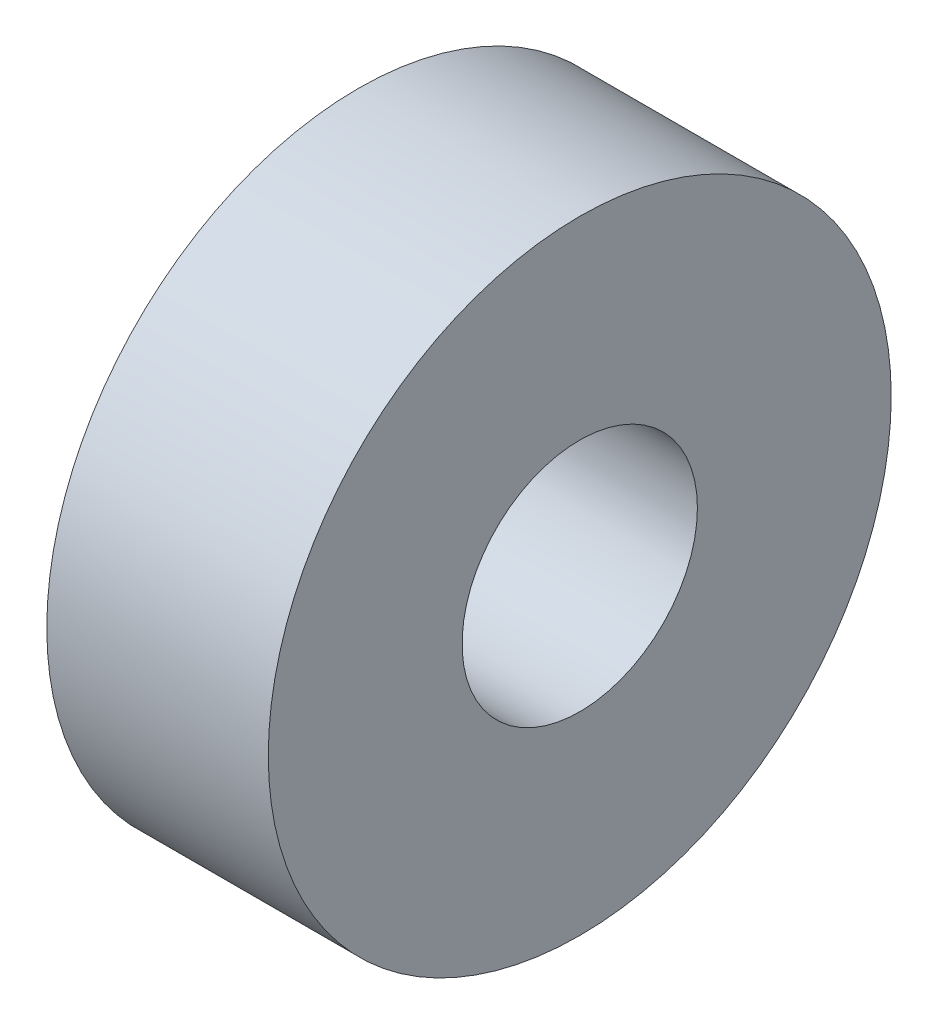
SolidWorks part; units mm, degrees
ref_plane "Спереди" through (0, 0, 0) normal (0, 0, 1) x (1, 0, 0)
ref_plane "Сверху" through (0, 0, 0) normal (0, 1, 0) x (1, 0, 0)
ref_plane "Справа" through (0, 0, 0) normal (1, 0, 0) x (0, 0, -1)
other "Configuration Table"
sketch "Эскиз1" plane through (0, 0, 0) normal (1, 0, 0) x (0, 0, -1)
  circle A0 centre (0, 0) radius 4.25
  circle A1 centre (0, 0) radius 11.25
  dimension "D1" = 8.5
  dimension "D2" = 22.5
extrude "Бобышка-Вытянуть1" add sketch "Эскиз1" along normal mid plane 8
